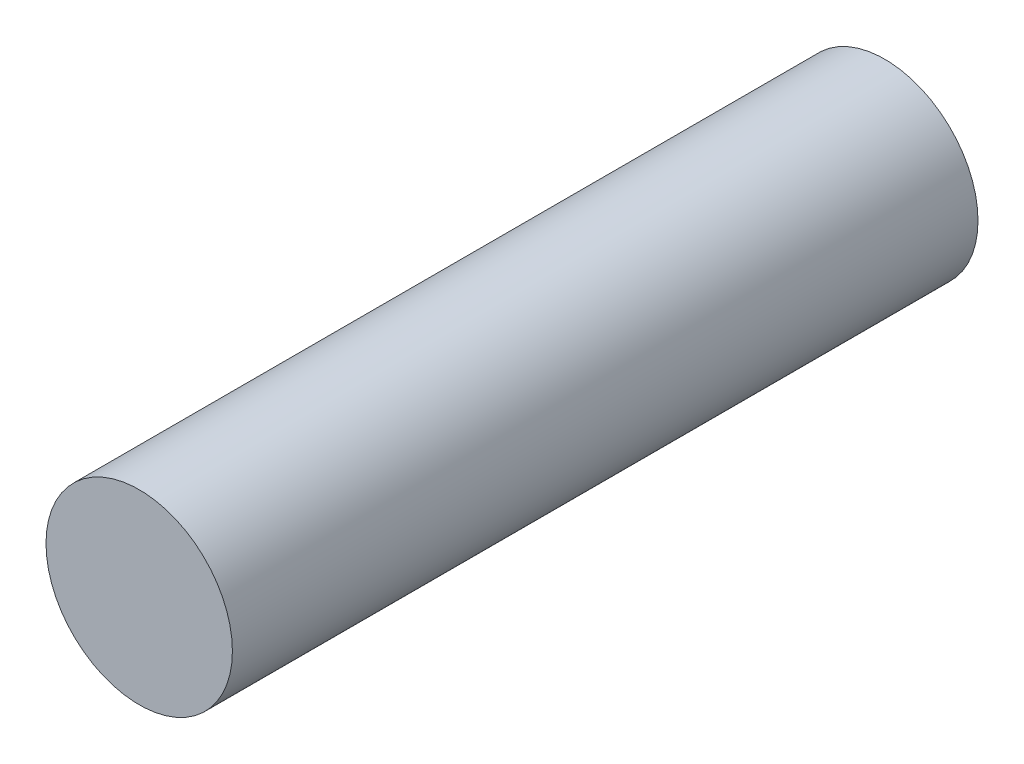
SolidWorks part; units mm, degrees
ref_plane "Front Plane" through (0, 0, 0) normal (0, 0, 1) x (1, 0, 0)
ref_plane "Top Plane" through (0, 0, 0) normal (0, 1, 0) x (1, 0, 0)
ref_plane "Right Plane" through (0, 0, 0) normal (1, 0, 0) x (0, 0, -1)
sketch "Sketch1" plane through (0, 0, 0) normal (0, 0, 1) x (1, 0, 0)
  circle A0 centre (0, 0) radius 3.175
  dimension "D1" = 6.35
extrude "Boss-Extrude1" add sketch "Sketch1" along normal blind 25.4
equation "\"Outer Diameter\"= 0.250"
equation "\"Outer Length\"= 1.0"
equation "\"D1@Sketch1\"=\"Outer Diameter\""
equation "\"D1@Boss-Extrude1\"=\"Outer Length\""
